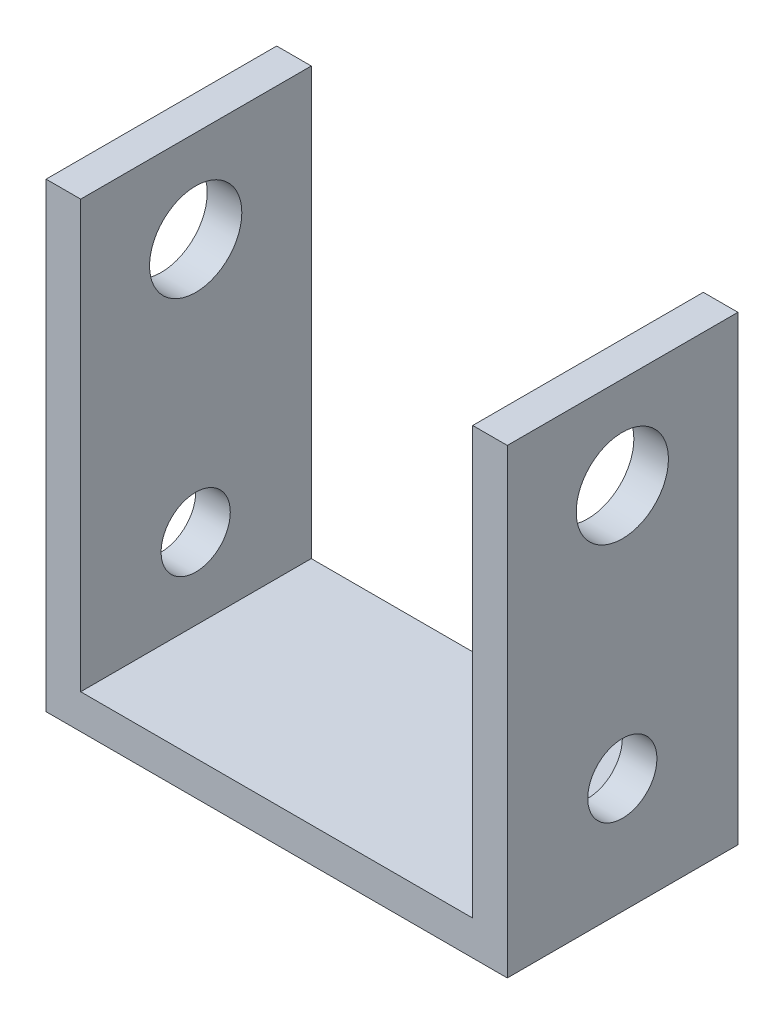
SolidWorks part; units mm, degrees
ref_plane "Plan de face" through (0, 0, 0) normal (0, 0, 1) x (1, 0, 0)
ref_plane "Plan de dessus" through (0, 0, 0) normal (0, 1, 0) x (1, 0, 0)
ref_plane "Plan de droite" through (0, 0, 0) normal (1, 0, 0) x (0, 0, -1)
sketch "Esquisse1" plane through (0, 0, 0) normal (0, 0, 1) x (1, 0, 0)
  line L0 (-26.8631, 18.8628) -> (-26.8631, -1.1372)
  line L1 (-26.8631, -1.1372) -> (-6.8631, -1.1372)
  line L2 (-6.8631, -1.1372) -> (-6.8631, 18.8628)
  line L3 (-6.8631, 18.8628) -> (-8.3631, 18.8628)
  line L4 (-8.3631, 18.8628) -> (-8.3631, 0.3628)
  line L5 (-8.3631, 0.3628) -> (-25.3631, 0.3628)
  line L6 (-25.3631, 0.3628) -> (-25.3631, 18.8628)
  line L7 (-25.3631, 18.8628) -> (-26.8631, 18.8628)
  dimension "D1" = 1.5
  dimension "D2" = 1.5
  dimension "D3" = 20
  dimension "D4" = 1.5
  dimension "D5" = 20
  dimension "D6" = 20
extrude "Extrusion1" add sketch "Esquisse1" along normal blind 10
sketch "Esquisse2" plane through (-6.8631, 0, 0) normal (1, 0, 0) x (0, 0, -1)
  line L0 (-5.0124, 14.8628) -> (-5.0124, 3.8628) construction
  line L1 (-10, 18.8628) -> (0, 18.8628) construction
  circle A0 centre (-5.0124, 14.8628) radius 2
  circle A1 centre (-5.0124, 3.8628) radius 1.5
  dimension "D1" = 11
  dimension "D2" = 4
extrude "Extrusion2" cut sketch "Esquisse2" against normal through all
